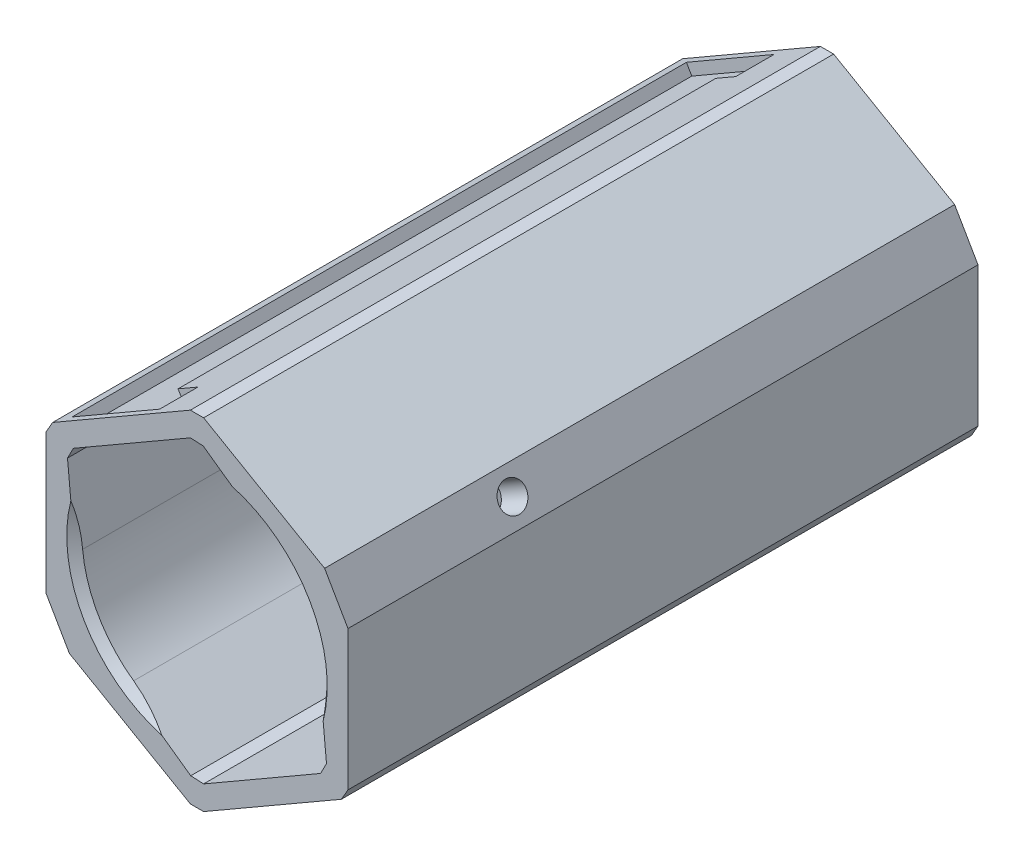
SolidWorks part; units mm, degrees
ref_plane "Front Plane" through (0, 0, 0) normal (0, 0, 1) x (1, 0, 0)
ref_plane "Top Plane" through (0, 0, 0) normal (0, 1, 0) x (1, 0, 0)
ref_plane "Right Plane" through (0, 0, 0) normal (1, 0, 0) x (0, 0, -1)
sketch "Sketch1" plane through (0, 0, 0) normal (0, 1, 0) x (1, 0, 0)
  line L0 (0, -39.84) -> (0, 48.538) construction
  line L1 (-48.4604, 0) -> (48.3051, 0) construction
  line L2 (0, 0) -> (16.125, 0)
  line L3 (16.125, 0) -> (16.125, -71)
  line L4 (16.125, -71) -> (19.65, -71)
  line L5 (19.65, -71) -> (19.65, 68)
  line L6 (19.65, 68) -> (24.95, 68)
  line L7 (24.95, 68) -> (24.95, 73)
  line L8 (24.95, 73) -> (28.1, 73)
  line L9 (28.1, 73) -> (28.1, 68)
  line L10 (28.1, 68) -> (42, 68)
  line L11 (42, 68) -> (42, 76)
  line L12 (42, 76) -> (16.65, 76)
  line L13 (16.65, 76) -> (16.65, 18.0044)
  line L14 (16.65, 18.0044) -> (12.194, 18.0044)
  line L15 (12.194, 18.0044) -> (12.194, 24.8827)
  line L16 (12.194, 24.8827) -> (0, 24.8827)
  line L17 (0, 0) -> (0, 24.8827)
  dimension "D1" = 42
  dimension "D2" = 8
  dimension "D3" = 16.125
  dimension "D4" = 19.65
  dimension "D5" = 71
  dimension "D6" = 68
  dimension "D7" = 5.3
  dimension "D8" = 3
  dimension "D9" = 3.15
  dimension "D10" = 68
  dimension "D11" = 5
revolve "Revolve1" add sketch "Sketch1" angle 360 about L0
sketch "Sketch2" plane through (0, 0, 71) normal (0, 0, 1) x (1, 0, 0)
  line L0 (0, 50.7794) -> (0, -52.6576) construction
  line L2 (0, 22.762) -> (-19.7125, 11.381)
  line L3 (-19.7125, 11.381) -> (-19.7125, -11.381)
  line L4 (-19.7125, -11.381) -> (0, -22.762)
  line L5 (0, -22.762) -> (19.7125, -11.381)
  line L6 (19.7125, -11.381) -> (19.7125, 11.381)
  line L7 (19.7125, 11.381) -> (0, 22.762)
  circle A0 centre (0, 0) radius 16
  circle A1 centre (0, 0) radius 19.7125 construction
  dimension "D1" = 32
  dimension "D2" = 39.425
extrude "Boss-Extrude1" add sketch "Sketch2" against normal blind 82.25
sketch "Sketch3" plane through (0, 0, 0) normal (0, 1, 0) x (1, 0, 0)
  line L0 (19.7125, -71) -> (0, -71) construction
  line L1 (-69.8468, 135.683) -> (82.1728, 135.683)
  line L2 (-69.8468, 135.683) -> (-69.8468, 11.25)
  line L3 (-69.8468, 11.25) -> (82.1728, 11.25)
  line L4 (82.1728, 135.683) -> (82.1728, 11.25)
  dimension "D1" = 82.25
extrude "Cut-Extrude1" cut sketch "Sketch3" against normal through all both and the other way through all
sketch "Sketch4" plane through (-9.8563, 17.0715, 0) normal (-0.5, 0.866, 0) x (0.866, 0.5, 0)
  line L0 (0, 22.8519) -> (0, -81.41) construction
  line L1 (11.381, -71) -> (-11.381, -71) construction
  line L2 (-8.6, 10.2) -> (4.6, 10.2)
  line L3 (-8.6, 10.2) -> (-8.6, -70)
  line L4 (-8.6, -70) -> (4.6, -70)
  line L5 (1.6, 5.2) -> (1.6, -65)
  line L6 (-3.5, 22.8519) -> (-3.5, -78.1641) construction
  line L8 (4.6, 10.2) -> (4.6, 5.2)
  line L9 (4.6, 5.2) -> (1.6, 5.2)
  line L10 (-54.3589, -29.9) -> (49.651, -29.9) construction
  line L11 (1.6, -65) -> (4.6, -65)
  line L12 (4.6, -65) -> (4.6, -70)
  dimension "D1" = 3
  dimension "D2" = 1
  dimension "D3" = 5.1
  dimension "D4" = 5.1
  dimension "D5" = 3.5
  dimension "D6" = 5
  dimension "D7" = 3
  dimension "D8" = 40.1
  dimension "D9" = 40.1
  dimension "D10" = 5
extrude "Cut-Extrude2" cut sketch "Sketch4" against normal blind 1.4
chamfer "Chamfer2" distance 1 6 edges at (0, -22.762, 29.875) (19.7125, -11.381, 29.875) (19.7125, 11.381, 29.875) (0, 22.762, 29.875) (-19.7125, -11.381, 29.875) (-19.7125, 11.381, 29.875)
chamfer "Chamfer3" distance 1 1 edges at (16, 0, 71)
sketch "Sketch5" plane through (0, 0, 71) normal (0, 0, 1) x (1, 0, 0)
  line L0 (0, 29.2623) -> (0, -28.2706) construction
  line L1 (-17, 9.815) -> (-15.9289, -1.507)
  line L8 (0, 19.6299) -> (-17, 9.815)
  line L11 (0, -19.6299) -> (17, -9.815)
  line L14 (-17, 9.815) -> (-17, -9.815) [skipped]
  line L15 (17, 9.815) -> (0, 19.6299) [skipped]
  line L16 (17, -9.815) -> (17, 9.815) [skipped]
  line L17 (-17, -9.815) -> (0, -19.6299) [skipped]
  line L18 (0, 19.6299) -> (9.2695, 13.0413)
  line L19 (0, -19.6299) -> (-9.2695, -13.0413)
  line L20 (17, -9.815) -> (15.9289, 1.507)
  circle A0 centre (0, 0) radius 17 construction
  arc A3 (-9.2695, -13.0413) -> (15.9289, 1.507) centre (0, 0) ccw
  arc A4 (9.2695, 13.0413) -> (-15.9289, -1.507) centre (0, 0) ccw
  dimension "D1" = 34
  dimension "D2" = 32
  dimension "D3" = 19.6299
  dimension "D4" = 19.6299
extrude "Cut-Extrude3" cut sketch "Sketch5" against normal up to surface (71 mm away) up to face at (16, 0, 0)
chamfer "Chamfer4" distance 1 4 edges at (0, -19.6299, 35.5) (17, -9.815, 35.5) (-17, 9.815, 35.5) (0, 19.6299, 35.5)
sketch "Sketch6" plane through (0, 0, -11.25) normal (0, 0, -1) x (-1, 0, 0)
  line L0 (0, 27.8377) -> (0, -30.1469) construction
  line L1 (-27.1417, 0) -> (27.0229, 0) construction
  line L8 (0, 0) -> (-7.2169, 12.5) construction
  line L9 (-7.2169, 12.5) -> (-14.4338, 0)
  line L10 (-14.4338, 0) -> (-7.2169, -12.5)
  line L11 (-7.2169, -12.5) -> (7.2169, -12.5)
  line L12 (7.2169, -12.5) -> (14.4338, 0)
  line L13 (14.4338, 0) -> (7.2169, 12.5)
  line L14 (7.2169, 12.5) -> (-7.2169, 12.5)
  circle A0 centre (0, 0) radius 12.5 construction
  dimension "D1" = 25
  dimension "D2" = 30
extrude "Cut-Extrude4" cut sketch "Sketch6" against normal blind 1.2
sketch "Sketch8" plane through (0, 0, -10.05) normal (0, 0, -1) x (-1, 0, 0)
  circle A0 centre (0, 0) radius 2.75
  dimension "D1" = 5.5
extrude "Cut-Extrude5" cut sketch "Sketch8" against normal through all
sketch "Sketch10" plane through (0, 0, 0) normal (0, 0, 1) x (1, 0, 0)
  line L0 (0, 11.9673) -> (0, -9.2947) construction
  line L1 (2.5, 10) -> (-2.5, 10)
  line L2 (-2.5, 10) -> (-2.5, 7.0711)
  line L3 (2.5, 10) -> (2.5, 7.0711)
  arc A0 (-2.5, 7.0711) -> (2.5, 7.0711) centre (0, 0) ccw
  point P9 (0, 10)
  dimension "D1" = 15
  dimension "D2" = 2.5
  dimension "D3" = 10
extrude "Cut-Extrude7" cut sketch "Sketch10" against normal blind 5
chamfer "Chamfer5" distance 0.5 4 edges at (2.5, 8.5355, 0) (0, 10, 0) (-2.5, 8.5355, 0) (0, -7.5, 0)
sketch "Sketch11" plane through (0, 0, 71) normal (0, 0, 1) x (1, 0, 0)
  line L0 (0, 0) -> (19.7125, 11.381) construction
  line L1 (-23.0929, 0) -> (26.2098, 0) construction
  line L2 (0, 0) -> (9.8563, -17.0715) construction
  line L9 (19.7125, 11.381) -> (16.6606, 13.1431)
  line L15 (0, 0) -> (0, 28.1304) construction
  line L16 (16.6606, 13.1431) -> (19.7125, 7.8569)
  line L18 (19.7125, 7.8569) -> (19.7125, 11.381)
  line L23 (-16.6606, -13.1431) -> (-19.7125, -11.381)
  line L24 (-19.7125, -7.8569) -> (-16.6606, -13.1431)
  line L25 (-19.7125, -11.381) -> (-19.7125, -7.8569)
  dimension "D1" = 30
  dimension "D3" = 21
extrude "Cut-Extrude8" cut sketch "Sketch11" against normal through all
sketch "Sketch12" plane through (-18.1865, -10.5, 0) normal (-0.866, -0.5, 0) x (0, 0, 1)
  line L0 (-22.307, 0) -> (76.3649, 0) construction
  line L1 (34, 27.3384) -> (34, -25.0984) construction
  line L2 (71, 18.8465) -> (71, 3.0519) construction
  line L3 (46, 31.7166) -> (46, -26.3202) construction
  circle A0 centre (48, 0) radius 1.8
  dimension "D3" = 3.6
  dimension "D1" = 37
  dimension "D2" = 12
  dimension "D4" = 2
extrude "Cut-Extrude9" cut sketch "Sketch12" against normal blind 4
sketch "Sketch13" plane through (18.1865, 10.5, 0) normal (0.866, 0.5, 0) x (0, 0, -1)
  circle A0 centre (-48, 0) radius 1.8 construction
  circle A1 centre (-48, 0) radius 1.8
extrude "Cut-Extrude10" cut sketch "Sketch13" against normal blind 4
